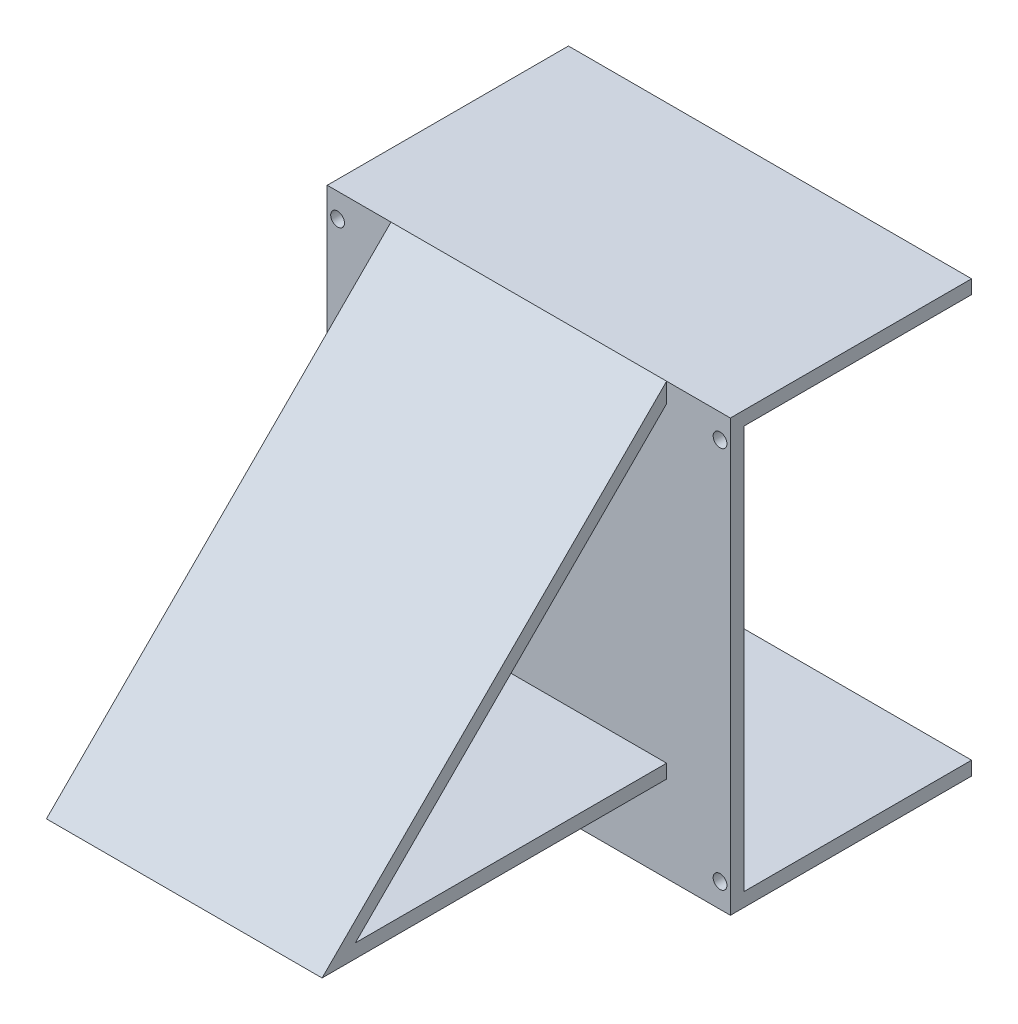
SolidWorks part; units mm, degrees
ref_plane "Ebene vorne" through (0, 0, 0) normal (0, 0, 1) x (1, 0, 0)
ref_plane "Ebene oben" through (0, 0, 0) normal (0, 1, 0) x (1, 0, 0)
ref_plane "Ebene rechts" through (0, 0, 0) normal (1, 0, 0) x (0, 0, -1)
sketch "Skizze1" plane through (0, 0, 0) normal (0, 0, 1) x (1, 0, 0)
  line L1 (0, 125) -> (117, 125)
  line L2 (0, 125) -> (0, 0)
  line L3 (0, 0) -> (117, 0)
  line L4 (117, 125) -> (117, 0)
  dimension "D1" = 117
  dimension "D2" = 125
extrude "Aufsatz-Linear austragen1" add sketch "Skizze1" along normal blind 4 contours L2 L1 L4 L3
sketch "Skizze2" plane through (0, 0, 4) normal (0, 0, 1) x (1, 0, 0)
  line L0 (18.5, 75) -> (0, 75) construction
  line L1 (18.5, 125) -> (98.5, 125)
  line L2 (18.5, 125) -> (18.5, 25)
  line L3 (18.5, 25) -> (98.5, 25)
  line L4 (98.5, 125) -> (98.5, 25)
  line L5 (0, 125) -> (0, 0) construction
  line L6 (98.5, 75) -> (117, 75) construction
  line L7 (117, 125) -> (117, 0) construction
  line L8 (0, 125) -> (117, 125) construction
  dimension "D1" = 80
  dimension "D2" = 100
extrude "Aufsatz-Linear austragen2" add sketch "Skizze2" along normal blind 100
sketch "Skizze3" plane through (18.5, 0, 0) normal (-1, 0, 0) x (0, 0, 1)
  line L0 (104, 25) -> (104, 125)
  line L1 (104, 125) -> (4, 125)
  line L2 (4, 125) -> (104, 25)
extrude "Schnitt-Linear austragen1" cut sketch "Skizze3" against normal blind 100
sketch "Skizze4" plane through (18.5, 0, 0) normal (-1, 0, 0) x (0, 0, 1)
  line L0 (4, 119.3431) -> (94.3431, 29)
  line L1 (94.3431, 29) -> (4, 29)
  line L2 (4, 29) -> (4, 119.3431)
  line L3 (4, 125) -> (104, 25) construction
  line L5 (104, 25) -> (4, 25) construction
  line L6 (4, 125) -> (4, 25) construction
  dimension "D1" = 4
  dimension "D3" = 4
extrude "Schnitt-Linear austragen2" cut sketch "Skizze4" against normal blind 100 contours L2 L0 L1
sketch "Skizze5" plane through (0, 0, 0) normal (0, 0, -1) x (-1, 0, 0)
  line L0 (0, 125) -> (-117, 125) construction
  line L1 (-117, 121) -> (0, 121)
  line L2 (-117, 121) -> (-117, 125)
  line L3 (-117, 125) -> (0, 125)
  line L4 (0, 121) -> (0, 125)
  line L5 (-117, 4) -> (0, 4)
  line L6 (-117, 4) -> (-117, 0)
  line L7 (-117, 0) -> (0, 0)
  line L8 (0, 4) -> (0, 0)
  point P8 (-117, 125)
  point P9 (0, 125)
  point P13 (-117, 0)
  point P15 (0, 0)
  dimension "D1" = 4
  dimension "D2" = 4
extrude "Aufsatz-Linear austragen3" add sketch "Skizze5" along normal blind 66
sketch "Skizze6" plane through (0, 0, 0) normal (0, 0, -1) x (-1, 0, 0)
  line L0 (-114, 118) -> (-3, 118) construction
  line L1 (-3, 118) -> (-3, 7) construction
  line L2 (-3, 7) -> (-114, 7) construction
  line L3 (-114, 7) -> (-114, 118) construction
  line L4 (-117, 121) -> (0, 4) construction
  line L5 (-117, 121) -> (-117, 4) construction
  line L6 (0, 121) -> (0, 4) construction
  circle A0 centre (-114, 118) radius 2
  circle A1 centre (-3, 118) radius 2
  circle A2 centre (-3, 7) radius 2
  circle A3 centre (-114, 7) radius 2
  point P2 (-114, 116.7065)
  point P15 (-114, 8.1484)
  point P18 (-3, 8.3162)
  point P20 (-31.4157, 82.5867)
  point P21 (-1.8359, 118)
  dimension "D1" = 3
  dimension "D2" = 3
extrude "Schnitt-Linear austragen3" cut sketch "Skizze6" against normal blind 70
